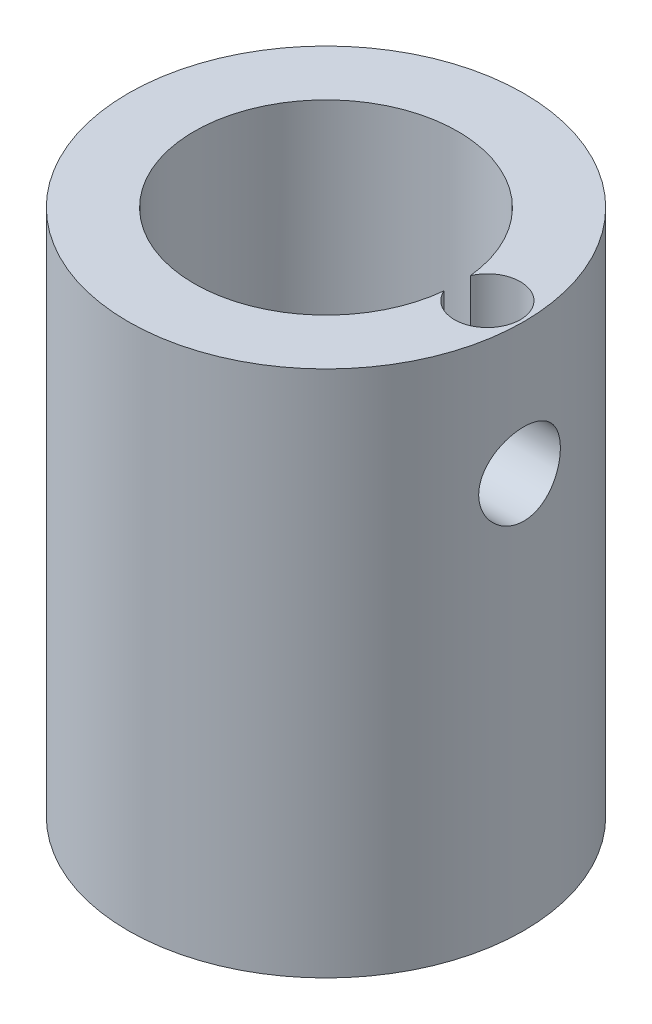
SolidWorks part; units mm, degrees
ref_plane "Front Plane" through (0, 0, 0) normal (0, 0, 1) x (1, 0, 0)
ref_plane "Top Plane" through (0, 0, 0) normal (0, 1, 0) x (1, 0, 0)
ref_plane "Right Plane" through (0, 0, 0) normal (1, 0, 0) x (0, 0, -1)
sketch "Sketch1" plane through (0, 0, 0) normal (0, 1, 0) x (1, 0, 0)
  circle A0 centre (0, 0) radius 30
  dimension "D1" = 60
extrude "Boss-Extrude1" add sketch "Sketch1" along normal blind 80
sketch "Sketch2" plane through (0, 80, 0) normal (0, 1, 0) x (1, 0, 0)
  circle A0 centre (0, 0) radius 20
  dimension "D1" = 40
extrude "Cut-Extrude2" cut sketch "Sketch2" against normal blind 77
sketch "Sketch3" plane through (0, 80, 0) normal (0, 1, 0) x (1, 0, 0)
  circle A0 centre (24.4796, 0) radius 5
  dimension "D1" = 10
extrude "Cut-Extrude3" cut sketch "Sketch3" against normal blind 20
sketch "Sketch6" plane through (0, 0, 0) normal (1, 0, 0) x (0, 0, -1)
  line L0 (0, 80) -> (0, 60) construction
  line L1 (30, 80) -> (-30, 80) construction
  circle A0 centre (0, 60) radius 6.1957
  dimension "D2" = 12.3914
  dimension "D1" = 20
extrude "Cut-Extrude6" cut sketch "Sketch6" along normal blind 40
